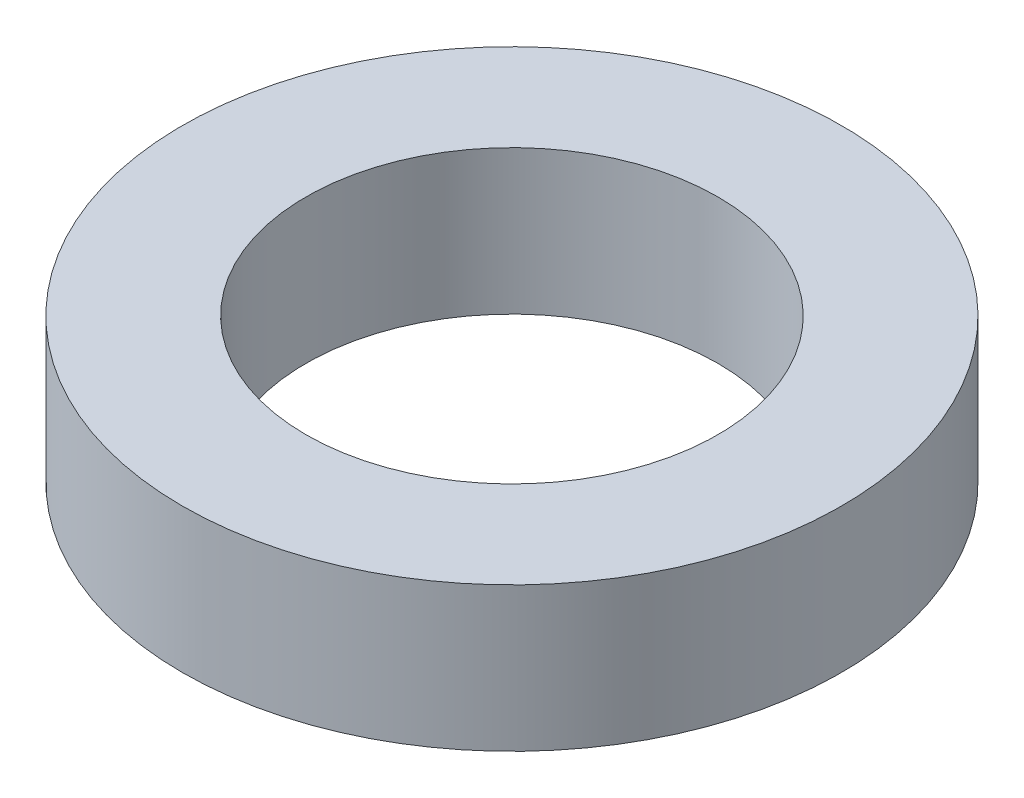
SolidWorks part; units mm, degrees
ref_plane "前视基准面" through (0, 0, 0) normal (0, 0, 1) x (1, 0, 0)
ref_plane "上视基准面" through (0, 0, 0) normal (0, 1, 0) x (1, 0, 0)
ref_plane "右视基准面" through (0, 0, 0) normal (1, 0, 0) x (0, 0, -1)
other "Configuration Table"
sketch "草图1" plane through (0, 0, 0) normal (0, 1, 0) x (1, 0, 0)
  circle A0 centre (0, 0) radius 10
  circle A1 centre (0, 0) radius 16
  dimension "D1" = 20
  dimension "D2" = 32
extrude "凸台-拉伸1" add sketch "草图1" along normal blind 7
